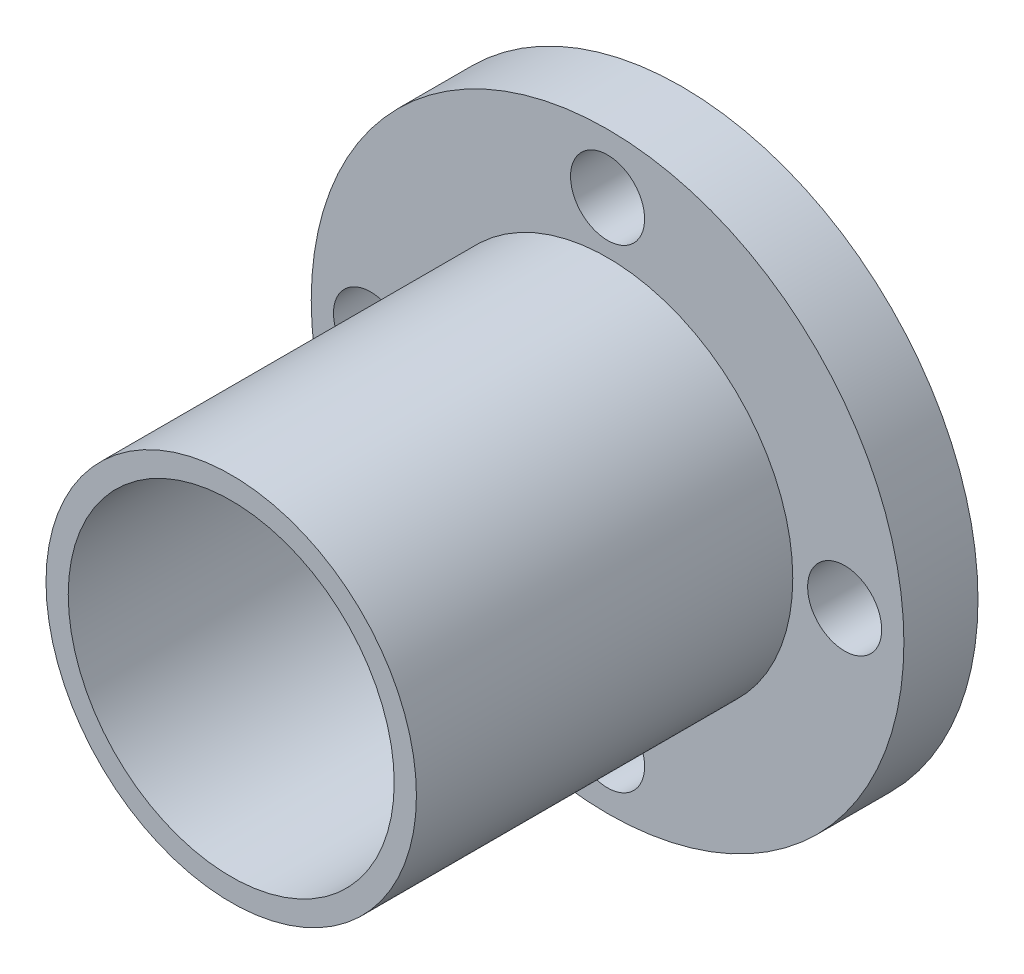
SolidWorks part; units mm, degrees
ref_plane "Front Plane" through (0, 0, 0) normal (0, 0, 1) x (1, 0, 0)
ref_plane "Top Plane" through (0, 0, 0) normal (0, 1, 0) x (1, 0, 0)
ref_plane "Right Plane" through (0, 0, 0) normal (1, 0, 0) x (0, 0, -1)
sketch "Sketch1" plane through (0, 0, 0) normal (0, 0, 1) x (1, 0, 0)
  line L0 (0, 0) -> (40, 0) construction
  line L1 (40, 0) -> (-40, 0) construction
  line L2 (0, 40) -> (0, -40) construction
  circle A0 centre (0, 0) radius 40
  circle A1 centre (0, -32) radius 5
  circle A2 centre (0, 32) radius 5
  circle A3 centre (-32, 0) radius 5
  circle A4 centre (32, 0) radius 5
  point P15 (-30, 0)
  dimension "D1" = 10
  dimension "D2" = 10
  dimension "D5" = 80
  dimension "D3" = 8
  dimension "D4" = 8
extrude "Boss-Extrude3" add sketch "Sketch1" along normal blind 10
sketch "Sketch3" plane through (0, 0, 10) normal (0, 0, 1) x (1, 0, 0)
  circle A0 centre (0, 0) radius 25
  circle A1 centre (0, 0) radius 22
  dimension "D1" = 50
  dimension "D2" = 44
extrude "Boss-Extrude4" add sketch "Sketch3" along normal blind 50.8
sketch "Sketch9" plane through (0, 0, 0) normal (0, 0, -1) x (-1, 0, 0)
  circle A0 centre (0, 0) radius 10
  dimension "D1" = 20
extrude "Cut-Extrude1" cut sketch "Sketch9" against normal blind 100
